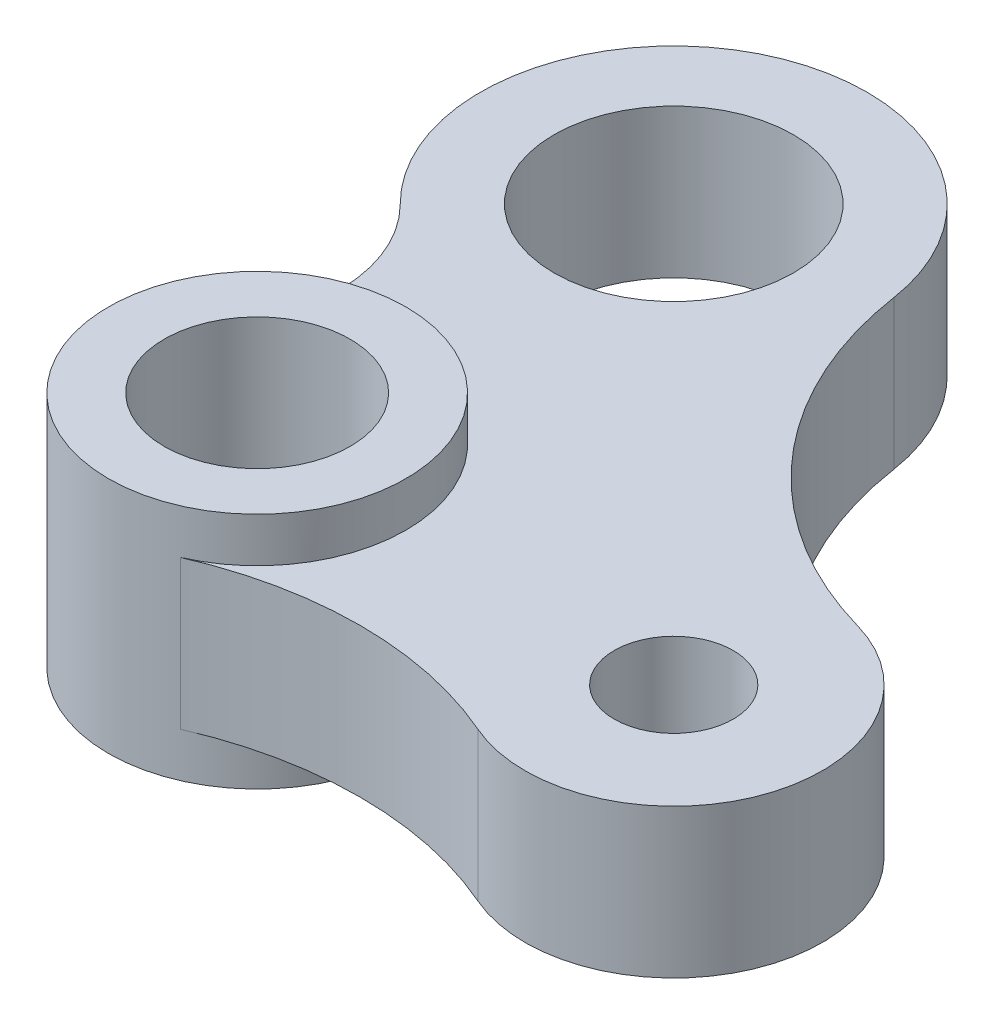
SolidWorks part; units mm, degrees
ref_plane "Alzado" through (0, 0, 0) normal (0, 0, 1) x (1, 0, 0)
ref_plane "Planta" through (0, 0, 0) normal (0, 1, 0) x (1, 0, 0)
ref_plane "Vista lateral" through (0, 0, 0) normal (1, 0, 0) x (0, 0, -1)
sketch "Croquis1" plane through (0, 0, 0) normal (0, 1, 0) x (1, 0, 0)
  line L0 (0, 0) -> (0, 28) construction
  line L1 (0, 0) -> (28, 0) construction
  arc A0 (-8.1116, 5.8482) -> (4, -9.1652) centre (0, 0) ccw
  arc A1 (0, 28) -> (28, 0) centre (0, 0) cw construction
  arc A2 (24, -9.1652) -> (30.7358, 9.6185) centre (28, 0) ccw
  arc A3 (12.8547, 29.9379) -> (-9.1697, 18.7849) centre (0, 28) ccw
  arc A4 (-8.1116, 5.8482) -> (-9.1697, 18.7849) centre (-16.2232, 11.6964) ccw
  arc A5 (12.8547, 29.9379) -> (30.7358, 9.6185) centre (37.5754, 33.6647) ccw
  arc A6 (24, -9.1652) -> (4, -9.1652) centre (14, -32.078) ccw
  dimension "D1" = 20
  dimension "D4" = 26
  dimension "D5" = 50
  dimension "D6" = 20
  dimension "D2" = 28
  dimension "D3" = 90
extrude "Saliente-Extruir1" add sketch "Croquis1" along normal blind 10
sketch "Croquis2" plane through (0, 10, 0) normal (0, 1, 0) x (1, 0, 0)
  line L0 (0, 0) -> (28, 0) construction
  line L1 (0, 0) -> (0, 28) construction
  circle A0 centre (0, 28) radius 8.05
  circle A1 centre (28, 0) radius 4
  dimension "D3" = 16.1
  dimension "D4" = 8
  dimension "D1" = 28
  dimension "D2" = 90
extrude "Cortar-Extruir1" cut sketch "Croquis2" against normal blind 10
sketch "Croquis3" plane through (0, 10, 0) normal (0, 1, 0) x (1, 0, 0)
  circle A0 centre (0, 0) radius 10
  dimension "D1" = 20
extrude "Saliente-Extruir2" add sketch "Croquis3" along normal blind 3
sketch "Croquis4" plane through (0, 0, 0) normal (0, -1, 0) x (1, 0, 0)
  circle A0 centre (0, 0) radius 10
  dimension "D1" = 20
extrude "Saliente-Extruir3" add sketch "Croquis4" along normal blind 3
sketch "Croquis5" plane through (0, 13, 0) normal (0, 1, 0) x (1, 0, 0)
  circle A0 centre (0, 0) radius 6.25
  dimension "D1" = 12.5
extrude "Cortar-Extruir2" cut sketch "Croquis5" against normal through all
